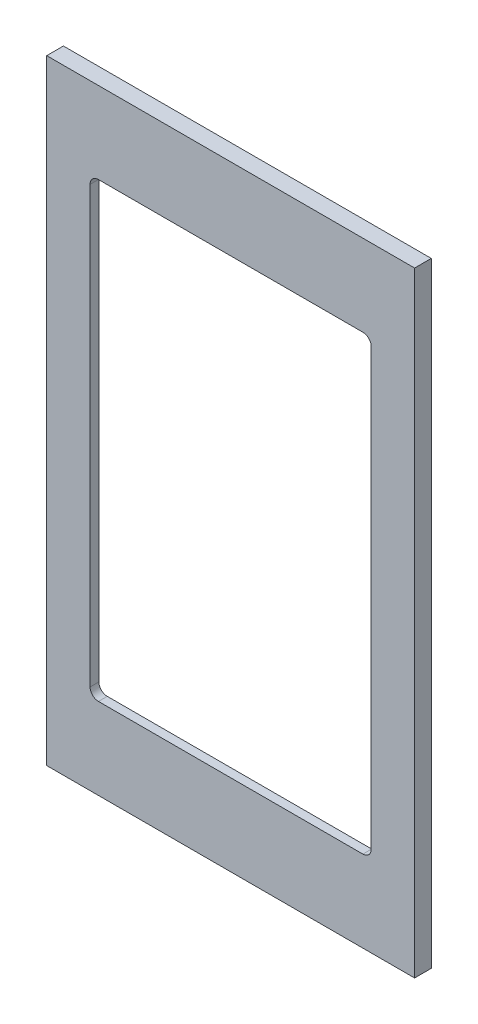
SolidWorks part; units mm, degrees
ref_plane "Front Plane" through (0, 0, 0) normal (0, 0, 1) x (1, 0, 0)
ref_plane "Top Plane" through (0, 0, 0) normal (0, 1, 0) x (1, 0, 0)
ref_plane "Right Plane" through (0, 0, 0) normal (1, 0, 0) x (0, 0, -1)
sketch "Sketch1" plane through (0, 0, 0) normal (0, 0, 1) x (1, 0, 0)
  line L1 (-70, 117) -> (70, 117)
  line L2 (-70, 117) -> (-70, -117)
  line L3 (-70, -117) -> (70, -117)
  line L4 (70, 117) -> (70, -117)
  line L5 (-70, 117) -> (70, -117) construction
  line L6 (-70, -117) -> (70, 117) construction
  point P0 (0, 0)
  dimension "D1" = 140
  dimension "D2" = 234
extrude "Boss-Extrude1" add sketch "Sketch1" along normal blind 6.35
sketch "Sketch2" plane through (0, 0, 6.35) normal (0, 0, 1) x (1, 0, 0)
  line L1 (-53.5, 86) -> (53.5, 86)
  line L2 (-53.5, 86) -> (-53.5, -86)
  line L3 (-53.5, -86) -> (53.5, -86)
  line L4 (53.5, 86) -> (53.5, -86)
  line L5 (-53.5, 86) -> (53.5, -86) construction
  line L6 (-53.5, -86) -> (53.5, 86) construction
  point P0 (0, 0)
  dimension "D1" = 172
  dimension "D2" = 107
extrude "Cut-Extrude1" cut sketch "Sketch2" against normal through all
fillet "Fillet1" radius 3.175 4 edges at (-53.5, -86, 3.175) (53.5, -86, 3.175) (53.5, 86, 3.175) (-53.5, 86, 3.175)
sketch "Sketch3" plane through (0, 0, 0) normal (0, 0, -1) x (-1, 0, 0)
  line L1 (-62.5, 105) -> (62.5, 105)
  line L2 (-62.5, 105) -> (-62.5, -105)
  line L3 (-62.5, -105) -> (62.5, -105)
  line L4 (62.5, 105) -> (62.5, -105)
  line L5 (-62.5, 105) -> (62.5, -105) construction
  line L6 (-62.5, -105) -> (62.5, 105) construction
  point P0 (0, 0)
  dimension "D1" = 210
  dimension "D2" = 125
extrude "Cut-Extrude2" cut sketch "Sketch3" against normal blind 3
fillet "Fillet2" radius 3.175 4 edges at (-62.5, -105, 1.5) (62.5, -105, 1.5) (-62.5, 105, 1.5) (62.5, 105, 1.5)
sketch "Sketch5" plane through (70, 0, 0) normal (1, 0, 0) x (0, 0, -1)
  line L1 (-3, 22) -> (3, 22)
  line L2 (-3, 22) -> (-3, -18)
  line L3 (-3, -18) -> (3, -18)
  line L4 (3, 22) -> (3, -18)
  line L5 (-3, 22) -> (3, -18) construction
  line L6 (-3, -18) -> (3, 22) construction
  line L7 (0, -117) -> (0, 117) construction
  line L10 (-6.35, 117) -> (0, 117) construction
  point P0 (0, 0)
  dimension "D1" = 40
  dimension "D2" = 3
  dimension "D3" = 95
extrude "Cut-Extrude4" cut sketch "Sketch5" against normal blind 20
sketch "Sketch6" plane through (0, 0, 3) normal (0, 0, -1) x (-1, 0, 0)
  line L0 (-70, 22) -> (-62.5, 22) construction
  line L1 (-69.5, 22) -> (-70, 22)
  line L2 (-69.5, 22) -> (-69.5, -18)
  line L3 (-69.5, -18) -> (-70, -18)
  line L4 (-70, 22) -> (-70, -18)
  dimension "D1" = 0.5
extrude "Boss-Extrude2" add sketch "Sketch6" along normal up to surface (3 mm away) up to face at (16.5625, 0.5, 0)
